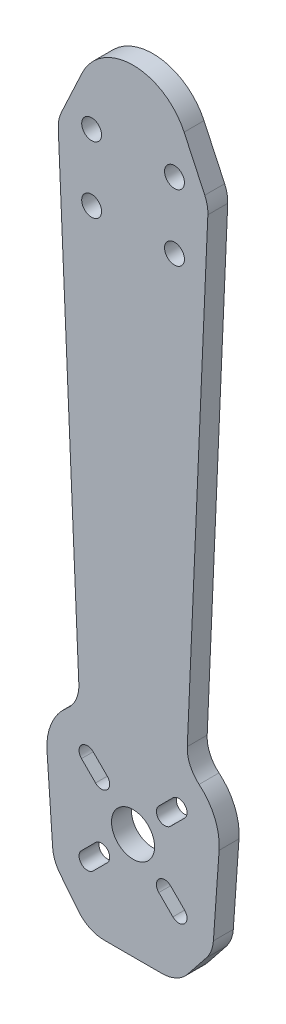
SolidWorks part; units mm, degrees
ref_plane "Front Plane" through (0, 0, 0) normal (0, 0, 1) x (1, 0, 0)
ref_plane "Top Plane" through (0, 0, 0) normal (0, 1, 0) x (1, 0, 0)
ref_plane "Right Plane" through (0, 0, 0) normal (1, 0, 0) x (0, 0, -1)
ref_plane "Plane1" through (0, 0, 0) normal (0, 0, -1) x (-1, 0, 0)
sketch "Sketch1" plane through (0, 0, 0) normal (0, 0, -1) x (-1, 0, 0)
  line L0 (8.1815, 15.5604) -> (11.2824, 86.5808)
  line L1 (10.8187, 88.912) -> (7.7036, 95.5923)
  line L2 (-7.7036, 95.5923) -> (-10.8187, 88.912)
  line L3 (-11.2824, 86.5808) -> (-8.1815, 15.5604)
  line L4 (-12.9793, 4.4071) -> (-12.1223, -7.8488)
  line L5 (-11.0475, -10.6126) -> (-8.2635, -14.1126)
  line L6 (-4.3504, -16) -> (4.3504, -16)
  line L7 (8.2635, -14.1126) -> (11.0475, -10.6126)
  line L8 (12.1223, -7.8488) -> (12.9793, 4.4071)
  line L9 (7.7782, 6.0104) -> (5.6569, 3.8891)
  line L10 (3.8891, 5.6569) -> (6.0104, 7.7782)
  line L11 (-5.6569, 3.8891) -> (-7.7782, 6.0104)
  line L12 (-6.0104, 7.7782) -> (-3.8891, 5.6569)
  line L13 (-3.8891, -5.6569) -> (-6.0104, -7.7782)
  line L14 (-7.7782, -6.0104) -> (-5.6569, -3.8891)
  line L15 (6.0104, -7.7782) -> (3.8891, -5.6569)
  line L16 (5.6569, -3.8891) -> (7.7782, -6.0104)
  circle A0 centre (0, 0) radius 3.25
  arc A1 (11.2824, 86.5808) -> (10.8187, 88.912) centre (6.2871, 86.7989) ccw
  arc A2 (7.7036, 95.5923) -> (-7.7036, 95.5923) centre (0, 92) ccw
  arc A3 (-10.8187, 88.912) -> (-11.2824, 86.5808) centre (-6.2871, 86.7989) ccw
  arc A4 (-8.1815, 15.5604) -> (-9.9632, 11.5118) centre (-13.1768, 15.3423) cw
  arc A5 (-9.9632, 11.5118) -> (-12.9793, 4.4071) centre (-4.5, 5) ccw
  arc A6 (-12.1223, -7.8488) -> (-11.0475, -10.6126) centre (-7.1345, -7.5) ccw
  arc A7 (-8.2635, -14.1126) -> (-4.3504, -16) centre (-4.3504, -11) ccw
  arc A8 (4.3504, -16) -> (8.2635, -14.1126) centre (4.3504, -11) ccw
  arc A9 (11.0475, -10.6126) -> (12.1223, -7.8488) centre (7.1345, -7.5) ccw
  arc A10 (12.9793, 4.4071) -> (9.9632, 11.5118) centre (4.5, 5) ccw
  arc A11 (9.9632, 11.5118) -> (8.1815, 15.5604) centre (13.1768, 15.3423) cw
  circle A12 centre (6.25, 89) radius 1.5
  circle A13 centre (6.25, 79) radius 1.5
  circle A14 centre (-6.25, 89) radius 1.5
  circle A15 centre (-6.25, 79) radius 1.5
  arc A16 (6.0104, 7.7782) -> (7.7782, 6.0104) centre (6.8943, 6.8943) cw
  arc A17 (5.6569, 3.8891) -> (3.8891, 5.6569) centre (4.773, 4.773) cw
  arc A18 (-7.7782, 6.0104) -> (-6.0104, 7.7782) centre (-6.8943, 6.8943) cw
  arc A19 (-3.8891, 5.6569) -> (-5.6569, 3.8891) centre (-4.773, 4.773) cw
  arc A20 (-5.6569, -3.8891) -> (-3.8891, -5.6569) centre (-4.773, -4.773) cw
  arc A21 (-6.0104, -7.7782) -> (-7.7782, -6.0104) centre (-6.8943, -6.8943) cw
  arc A22 (7.7782, -6.0104) -> (6.0104, -7.7782) centre (6.8943, -6.8943) cw
  arc A23 (3.8891, -5.6569) -> (5.6569, -3.8891) centre (4.773, -4.773) cw
extrude "Boss-Extrude1" add sketch "Sketch1" against normal blind 3
